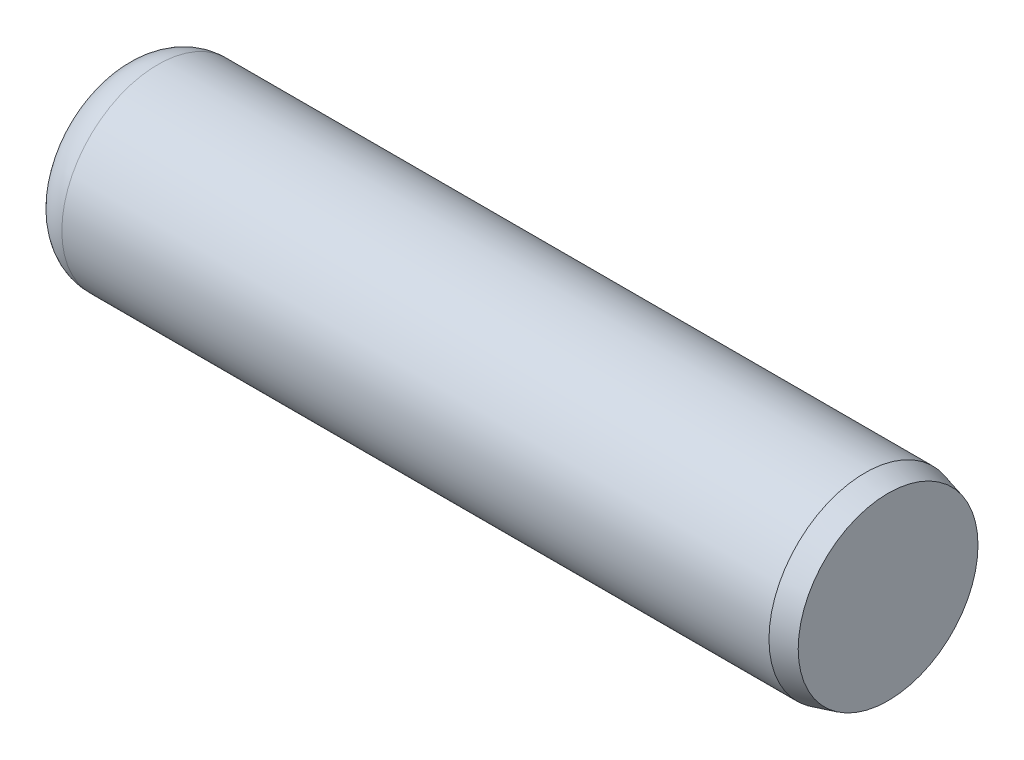
SolidWorks part; units mm, degrees
ref_plane "Plane1" through (0, 0, 0) normal (0, 0, 1) x (1, 0, 0)
ref_plane "Plane2" through (0, 0, 0) normal (0, 1, 0) x (1, 0, 0)
ref_plane "Plane3" through (0, 0, 0) normal (1, 0, 0) x (0, 0, -1)
sketch "Sketch1" plane through (0, 0, 0) normal (0, 0, 1) x (1, 0, 0)
  line L1 (-6.35, 0) -> (107.95, 0) construction
  line L2 (0, 0) -> (101.6, 0)
  line L3 (101.6, 0) -> (101.6, 11.8833)
  line L4 (101.6, 11.8833) -> (98.552, 12.7)
  line L5 (98.552, 12.7) -> (5.08, 12.7)
  line L6 (0, 7.62) -> (0, 0)
  arc A0 (5.08, 12.7) -> (0, 7.62) centre (5.08, 7.62) ccw
  dimension "D4" = 5.08
  dimension "Length" = 101.6
  dimension "D2" = 3.048
  dimension "D3" = 15
  dimension "Diameter" = 25.4
revolve "Base-Revolve" add sketch "Sketch1" angle 360 about L1
equation "\"D4@Sketch1\" = \"Diameter@Sketch1\" * 0.2"
equation "\"D2@Sketch1\" = \"Diameter@Sketch1\" * 0.12"
equation "\"D3@Sketch1\" = 15.0"
